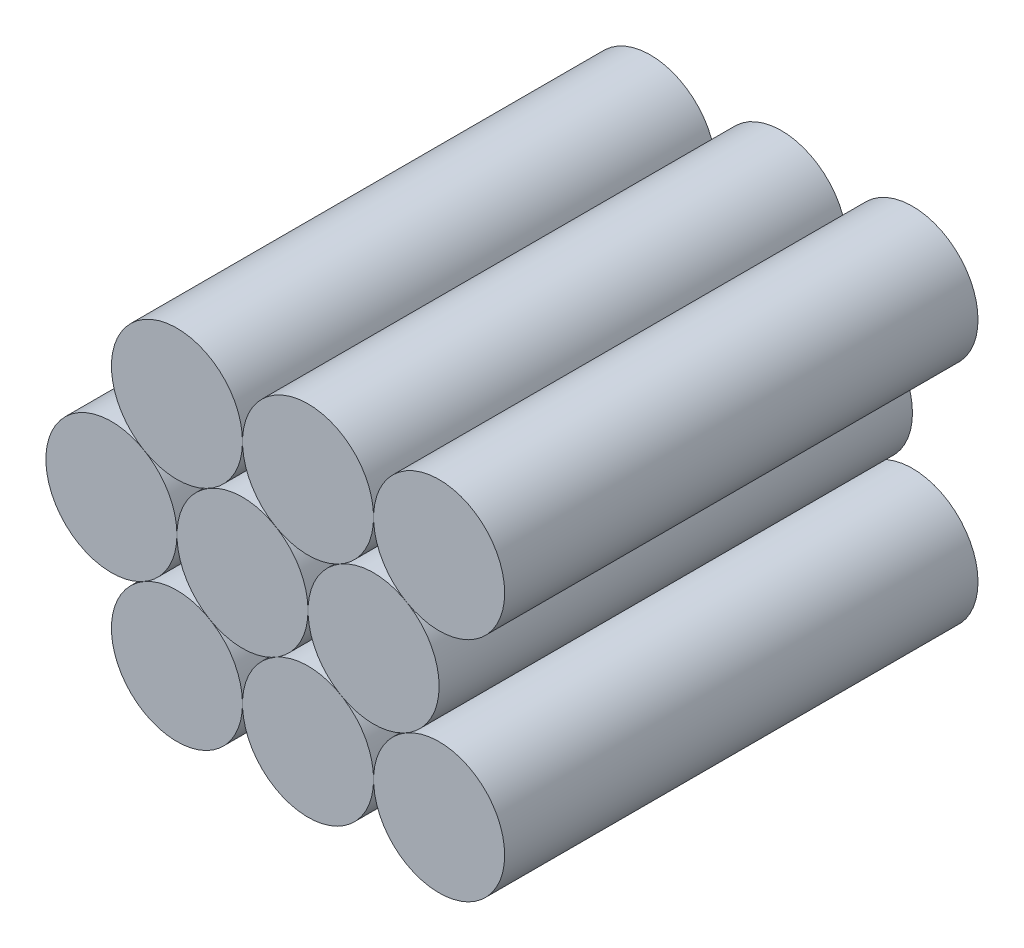
SolidWorks part; units mm, degrees
ref_plane "Plan de face" through (0, 0, 0) normal (0, 0, 1) x (1, 0, 0)
ref_plane "Plan de dessus" through (0, 0, 0) normal (0, 1, 0) x (1, 0, 0)
ref_plane "Plan de droite" through (0, 0, 0) normal (1, 0, 0) x (0, 0, -1)
sketch "Esquisse1" plane through (0, 0, 0) normal (0, 0, 1) x (1, 0, 0)
  line L0 (-27, 0) -> (-9, 0) construction
  line L1 (-9, 0) -> (9, 0) construction
  line L2 (-18, 15.5885) -> (0, 15.5885) construction
  line L3 (0, 15.5885) -> (18, 15.5885) construction
  line L4 (18, 15.5885) -> (36, 15.5885) construction
  line L5 (9, 0) -> (27, 0) construction
  line L6 (-18, 0) -> (-9, 15.5885) construction
  line L7 (36, -15.5885) -> (18, -15.5885) construction
  line L8 (18, -15.5885) -> (0, -15.5885) construction
  line L9 (0, -15.5885) -> (-18, -15.5885) construction
  line L10 (-9, 15.5885) -> (0, 0) construction
  line L11 (-18, 0) -> (-9, -15.5885) construction
  line L12 (-9, -15.5885) -> (0, 0) construction
  circle A0 centre (0, 0) radius 9
  circle A1 centre (18, 0) radius 9
  circle A2 centre (-18, 0) radius 9
  circle A3 centre (-9, 15.5885) radius 9
  circle A4 centre (9, 15.5885) radius 9
  circle A5 centre (27, 15.5885) radius 9
  circle A6 centre (-9, -15.5885) radius 9
  circle A7 centre (9, -15.5885) radius 9
  circle A8 centre (27, -15.5885) radius 9
  dimension "D1" = 18
extrude "Boss.-Extru.1" add sketch "Esquisse1" along normal blind 65 contours A2 | A3 | A0 | A4 | A5 | A1 | A7 | A6 | A8
